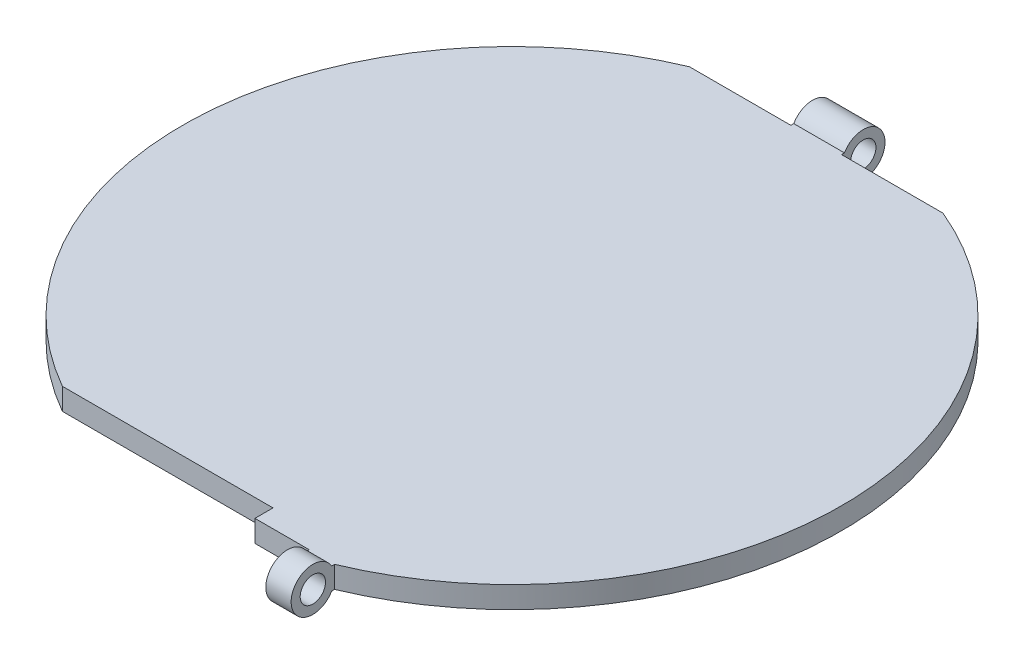
SolidWorks part; units mm, degrees
ref_plane "Front Plane" through (0, 0, 0) normal (0, 0, 1) x (1, 0, 0)
ref_plane "Top Plane" through (0, 0, 0) normal (0, 1, 0) x (1, 0, 0)
ref_plane "Right Plane" through (0, 0, 0) normal (1, 0, 0) x (0, 0, -1)
sketch "Sketch1" plane through (0, 0, 0) normal (0, 1, 0) x (1, 0, 0)
  line L0 (-17.5, -42) -> (17.5, -42)
  line L1 (0, 0) -> (36.3754, 0) construction
  line L2 (-17.5, 42) -> (17.5, 42)
  arc A0 (-17.5, 42) -> (-17.5, -42) centre (0, 0) ccw
  arc A1 (17.5, -42) -> (17.5, 42) centre (0, 0) ccw
  dimension "D1" = 91
  dimension "D2" = 42
  dimension "D3" = 42
extrude "Boss-Extrude1" add sketch "Sketch1" along normal blind 3
sketch "Sketch2" plane through (0, 0, 0) normal (1, 0, 0) x (0, 0, -1)
  line L0 (-43.0566, 1.5) -> (50.2125, 1.5) construction
  line L1 (-42, 3) -> (-42, 0) construction
  line L2 (-42, 0) -> (-42.4019, 0)
  line L3 (-42, 0) -> (42, 0) construction
  line L4 (-42, 0) -> (-42, 1.5)
  line L5 (-42, 1.5) -> (-42, 3)
  line L6 (-42, 3) -> (-42.4019, 3)
  line L7 (42, 3) -> (-42, 3) construction
  circle A0 centre (-45, 1.5) radius 1.75
  arc A1 (-42.4019, 3) -> (-42.4019, 0) centre (-45, 1.5) ccw
  point P4 (-42, 1.5)
  dimension "D1" = 6
  dimension "D2" = 3.5
extrude "Boss-Extrude2" add sketch "Sketch2" along normal blind 17.5 and the other way blind 10
mirror "Mirror1" about plane through (0, 0, 0) normal (0, 0, 1) of "Boss-Extrude2"
sketch "Sketch3" plane through (-10, 0, 0) normal (-1, 0, 0) x (0, 0, 1)
  line L0 (42, 0) -> (42, 3) construction
  line L1 (42, 6.5) -> (50, 6.5)
  line L2 (42, 6.5) -> (42, -2.5)
  line L3 (42, -2.5) -> (50, -2.5)
  line L4 (50, 6.5) -> (50, -2.5)
  circle A0 centre (45, 1.5) radius 1.75 construction
  dimension "D1" = 9
  dimension "D2" = 8
  dimension "D3" = 5
extrude "Cut-Extrude1" cut sketch "Sketch3" against normal blind 24
sketch "Sketch4" plane through (-10, 0, 0) normal (-1, 0, 0) x (0, 0, 1)
  line L5 (-42, 0) -> (-42, 3) construction
  line L6 (-42, -2.5) -> (-50, -2.5)
  line L7 (-42, -2.5) -> (-42, 6.5)
  line L8 (-42, 6.5) -> (-50, 6.5)
  line L10 (-50, 6.5) -> (-50, -2.5)
  circle A0 centre (-45, 1.5) radius 1.75 construction
  dimension "D1" = 8
  dimension "D2" = 9
  dimension "D3" = 5
extrude "Cut-Extrude2" cut sketch "Sketch4" against normal blind 6.5
ref_plane "Plane1" through (6.5, 0, 0) normal (-1, 0, 0) x (0, 0, 1)
sketch "Sketch5" plane through (17.5, 0, 0) normal (1, 0, 0) x (0, 0, -1)
  line L0 (42, 3) -> (42, 0) construction
  line L1 (42, 5.0896) -> (49, 5.0896)
  line L2 (42, 5.0896) -> (42, -1.9104)
  line L3 (42, -1.9104) -> (49, -1.9104)
  line L4 (49, 5.0896) -> (49, -1.9104)
  arc A0 (42.4019, 0) -> (42.4019, 3) centre (45, 1.5) ccw construction
  dimension "D1" = 7
  dimension "D2" = 7
  dimension "D3" = 3.5896
extrude "Cut-Extrude3" cut sketch "Sketch5" against normal blind 14
sketch "Sketch6" plane through (6.5, 0, 0) normal (-1, 0, 0) x (0, 0, 1)
  line L1 (39.5, 7.5) -> (50.5, 7.5)
  line L2 (39.5, 7.5) -> (39.5, -4.5)
  line L3 (39.5, -4.5) -> (50.5, -4.5)
  line L4 (50.5, 7.5) -> (50.5, -4.5)
  point P4 (45, 1.5)
  point P7 (45, 7.5)
  point P8 (50.5, 1.5)
  dimension "D1" = 11
  dimension "D2" = 12
extrude "Cut-Extrude4" cut sketch "Sketch6" along normal up to surface up to face at (-31.5, 1.5, 0)
